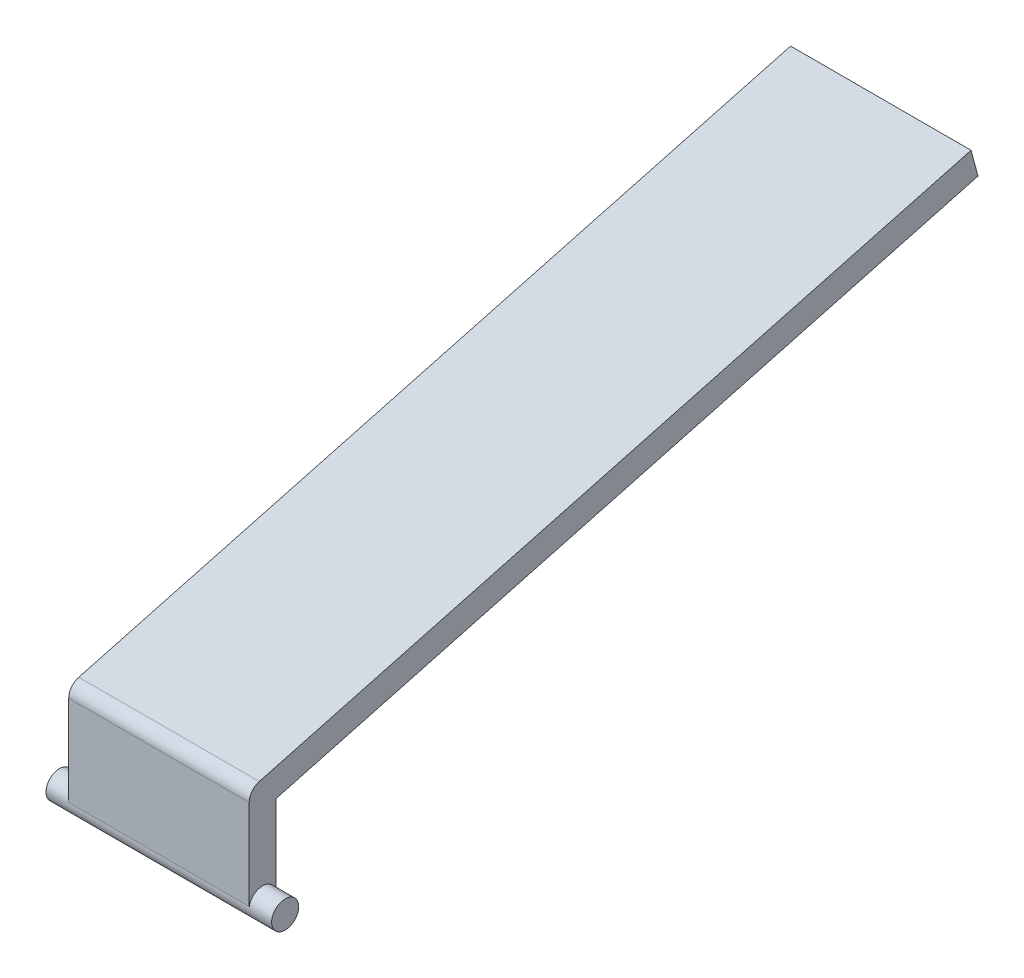
SolidWorks part; units mm, degrees
ref_plane "Front Plane" through (0, 0, 0) normal (0, 0, 1) x (1, 0, 0)
ref_plane "Top Plane" through (0, 0, 0) normal (0, 1, 0) x (1, 0, 0)
ref_plane "Right Plane" through (0, 0, 0) normal (1, 0, 0) x (0, 0, -1)
sketch "Sketch1" plane through (0, 0, 0) normal (1, 0, 0) x (0, 0, -1)
  circle A0 centre (0, 0) radius 0.3
extrude "Boss-Extrude1" add sketch "Sketch1" along normal mid plane 5
sketch "Sketch2" plane through (0, 0, 0) normal (1, 0, 0) x (0, 0, -1)
  line L0 (-0.2962, 0.0475) -> (-0.2962, 2.0475)
  line L1 (-0.0726, 2.3389) -> (15.7, 6.5652)
  line L2 (15.7, 6.5652) -> (15.8533, 5.993)
  line L4 (0.2962, 1.8244) -> (0.2962, 0.0475)
  line L5 (0.2962, 0.0475) -> (-0.2962, 0.0475)
  line L6 (0.2962, 1.8244) -> (15.8533, 5.993)
  circle A0 centre (0, 0) radius 0.3 construction
  arc A1 (-0.2962, 2.0475) -> (-0.0726, 2.3389) centre (0.0055, 2.0475) cw
  dimension "D1" = 75
  dimension "D2" = 15.7
  dimension "D3" = 2
extrude "Boss-Extrude2" add sketch "Sketch2" along normal blind 2 and the other way blind 2
